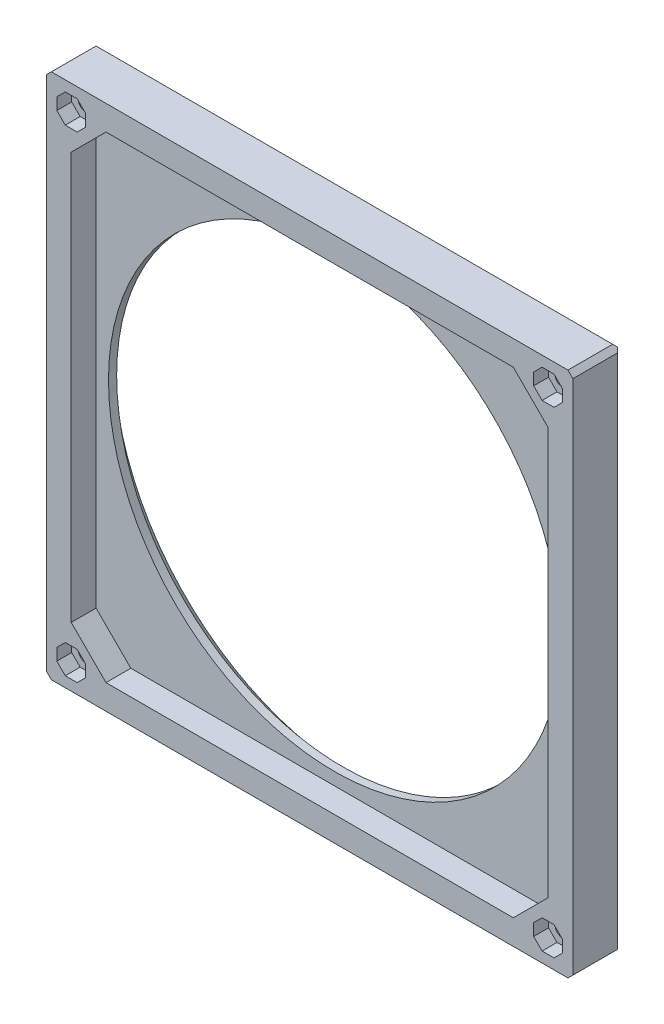
SolidWorks part; units mm, degrees
ref_plane "Front Plane" through (0, 0, 0) normal (0, 0, 1) x (1, 0, 0)
ref_plane "Top Plane" through (0, 0, 0) normal (0, 1, 0) x (1, 0, 0)
ref_plane "Right Plane" through (0, 0, 0) normal (1, 0, 0) x (0, 0, -1)
sketch "Sketch1 larger dia" plane through (0, 0, 0) normal (0, 0, 1) x (1, 0, 0)
  line L0 (-41, 48) -> (41, 48)
  line L1 (-53, 53) -> (53, 53)
  line L2 (-53, 53) -> (-53, -53)
  line L3 (-53, -53) -> (53, -53)
  line L4 (53, 53) -> (53, -53)
  line L5 (41, 48) -> (48, 41)
  line L6 (48, 41) -> (48, -41)
  line L7 (48, -41) -> (41, -48)
  line L8 (41, -48) -> (-41, -48)
  line L9 (-41, -48) -> (-48, -41)
  line L10 (-48, -41) -> (-48, 41)
  line L11 (-48, 41) -> (-41, 48)
  dimension "D2" = 12
  dimension "D3" = 5
  dimension "D4" = 5
  dimension "D5" = 5
  dimension "D6" = 5
  dimension "D8" = 12
  dimension "D9" = 12
  dimension "D10" = 12
  dimension "D11" = 12
  dimension "D12" = 12
sketch "Sketch3 holes" plane through (0, 0, 0) normal (0, 0, 1) x (1, 0, 0)
  line L1 (-53, 53) -> (53, 53) construction
  line L2 (-53, 53) -> (-53, -53) construction
  line L3 (-53, -53) -> (53, -53) construction
  line L4 (53, 53) -> (53, -53) construction
  circle A0 centre (-48, 48) radius 1.6
  circle A1 centre (48, 48) radius 1.6
  circle A2 centre (-48, -48) radius 1.6
  circle A3 centre (48, -48) radius 1.6
  dimension "D1" = 5
  dimension "D3" = 3.2
  dimension "D6" = 3.2
  dimension "D9" = 3.2
  dimension "D12" = 3.2
  dimension "D2" = 5
  dimension "D4" = 5
  dimension "D5" = 5
  dimension "D7" = 5
  dimension "D8" = 5
  dimension "D10" = 5
  dimension "D11" = 5
sketch "Sketch4 ring" plane through (0, 0, 0) normal (0, 0, 1) x (1, 0, 0)
  circle A0 centre (0, 0) radius 47.75
  circle A1 centre (0, 0) radius 45.5
  dimension "D1" = 95.5
  dimension "D2" = 91
extrude "Boss-Extrude1" add sketch "Sketch1 larger dia" along normal blind 5
sketch "Sketch5 smaller dia" plane through (0, 0, 0) normal (0, 0, -1) x (-1, 0, 0)
  line L1 (-53, 53) -> (53, 53)
  line L2 (-53, 53) -> (-53, -53)
  line L3 (-53, -53) -> (53, -53)
  line L4 (53, 53) -> (53, -53)
  circle A0 centre (0, 0) radius 45.5
  dimension "D1" = 91
extrude "Boss-Extrude2" add sketch "Sketch5 smaller dia" along normal blind 5
sketch "Sketch1" plane through (0, 0, 5) normal (0, 0, 1) x (1, 0, 0)
  line L0 (0, 53) -> (0, -53) construction
  line L1 (-53, 53) -> (53, 53) construction
  line L2 (-53, 53) -> (-53, -53) construction
  line L3 (-53, -53) -> (53, -53) construction
  line L4 (53, 53) -> (53, -53) construction
  line L5 (-45.1, 46.7988) -> (-45.1, 49.2012)
  line L6 (-45.1, 49.2012) -> (-46.7988, 50.9)
  line L7 (-46.7988, 50.9) -> (-49.2012, 50.9)
  line L8 (-49.2012, 50.9) -> (-50.9, 49.2012)
  line L9 (-50.9, 49.2012) -> (-50.9, 46.7988)
  line L10 (-50.9, 46.7988) -> (-49.2012, 45.1)
  line L11 (-49.2012, 45.1) -> (-46.7988, 45.1)
  line L12 (-46.7988, 45.1) -> (-45.1, 46.7988)
  line L13 (-53, 0) -> (53, 0) construction
  line L14 (-46.7988, -45.1) -> (-45.1, -46.7988)
  line L15 (-49.2012, -45.1) -> (-46.7988, -45.1)
  line L16 (-50.9, -46.7988) -> (-49.2012, -45.1)
  line L17 (-50.9, -49.2012) -> (-50.9, -46.7988)
  line L18 (-49.2012, -50.9) -> (-50.9, -49.2012)
  line L19 (-46.7988, -50.9) -> (-49.2012, -50.9)
  line L20 (-45.1, -49.2012) -> (-46.7988, -50.9)
  line L21 (-45.1, -46.7988) -> (-45.1, -49.2012)
  line L22 (46.7988, 45.1) -> (45.1, 46.7988)
  line L23 (49.2012, 45.1) -> (46.7988, 45.1)
  line L24 (50.9, 46.7988) -> (49.2012, 45.1)
  line L25 (50.9, 49.2012) -> (50.9, 46.7988)
  line L26 (49.2012, 50.9) -> (50.9, 49.2012)
  line L27 (46.7988, 50.9) -> (49.2012, 50.9)
  line L28 (45.1, 49.2012) -> (46.7988, 50.9)
  line L29 (45.1, 46.7988) -> (45.1, 49.2012)
  line L30 (45.1, -46.7988) -> (45.1, -49.2012)
  line L31 (45.1, -49.2012) -> (46.7988, -50.9)
  line L32 (46.7988, -50.9) -> (49.2012, -50.9)
  line L33 (49.2012, -50.9) -> (50.9, -49.2012)
  line L34 (50.9, -49.2012) -> (50.9, -46.7988)
  line L35 (50.9, -46.7988) -> (49.2012, -45.1)
  line L36 (49.2012, -45.1) -> (46.7988, -45.1)
  line L37 (46.7988, -45.1) -> (45.1, -46.7988)
  circle A4 centre (-48, 48) radius 2.9 construction
  circle A5 centre (-48, -48) radius 2.9 construction
  circle A6 centre (48, 48) radius 2.9 construction
  circle A7 centre (48, -48) radius 2.9 construction
  dimension "D3" = 5
  dimension "D13" = 5.8
  dimension "D2" = 5
  dimension "D4" = 106
extrude "Cut-Extrude1" cut sketch "Sketch1" against normal blind 3
chamfer "Chamfer1" distance 4 angle 40 1 edges at (-45.5, 0, -5)
chamfer "Chamfer2" distance 1 4 edges at (0, -53, -5) (53, 0, -5) (0, 53, -5) (-53, 0, -5)
chamfer "Chamfer3" distance 1 angle 45 4 edges at (53, -53, 0.5) (-53, -53, 0.5) (-53, 53, 0.5) (53, 53, 0.5)
extrude "Cut-Extrude2" cut sketch "Sketch3 holes" against normal blind 2 and the other way blind 10
